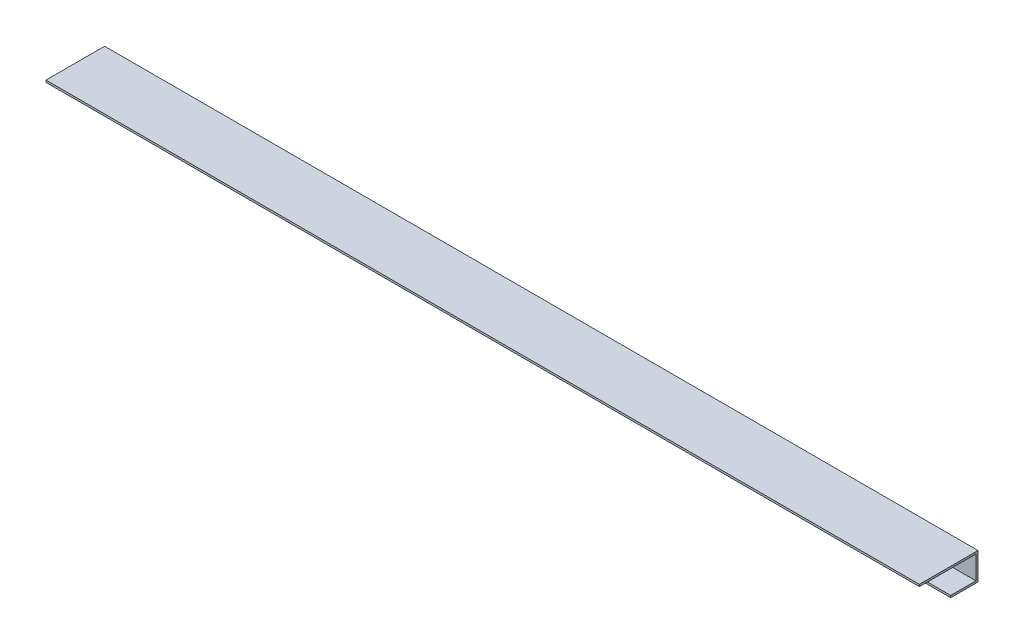
SolidWorks part; units mm, degrees
ref_plane "Front Plane" through (0, 0, 0) normal (0, 0, 1) x (1, 0, 0)
ref_plane "Top Plane" through (0, 0, 0) normal (0, 1, 0) x (1, 0, 0)
ref_plane "Right Plane" through (0, 0, 0) normal (1, 0, 0) x (0, 0, -1)
sketch "Sketch1" plane through (0, 0, 0) normal (1, 0, 0) x (0, 0, -1)
  line L0 (0, 0) -> (58, 0)
  line L1 (58, 0) -> (58, -27)
  line L2 (58, -27) -> (31, -27)
  line L3 (0, -2) -> (56, -2)
  line L4 (56, -2) -> (56, -25)
  line L5 (56, -25) -> (31, -25)
  line L6 (0, 0) -> (0, -2)
  line L7 (31, -25) -> (31, -27)
  dimension "D1" = 2
  dimension "D2" = 58
  dimension "D3" = 27
  dimension "D4" = 27
extrude "Boss-Extrude1" add sketch "Sketch1" along normal blind 864
equation "\"door_base_short7_R1_R_open_Single_width\"=864"
equation "\"D1@Boss-Extrude1\"=\"door_base_short7_R1_R_open_Single_width\""
equation "\"CarBeamWidth\"=700.0"
equation "\"WheelWidth\"=650.0"
equation "\"Wheel_FrontBoxDistance\"=1390.0"
equation "\"MetalSheet_3mm_length\"=5030.0"
equation "\"MetalSheet_3mm_width\"=1923.0"
equation "\"MetalSheet_3mm_FloorCut_L_length\"=1764.0"
equation "\"MetalSheet_3mm_FloorCut_L_disdance\"=1665.0"
equation "\"MetalSheet_3mm_FloorCut_R_length\"=1764.0"
equation "\"MetalSheet_3mm_FloorCut_R_disdance\"=1665.0"
equation "\"indoorHeight\"=1940.0"
equation "\"haveDoor_R\"=1"
equation "\"side_door_bottom_R_3mm_length\"=1934.0"
equation "\"1Bar_Side_RF_3mm_length\"=1493.0"
equation "\"1Bar_Side_RB_3mm_length\"=1493.0"
equation "\"DoorSeparator_RF_3mm_withHinge_toFrontDistance\"=1673.0"
equation "\"DoorSeparator_RF_3mm_withHinge_exist\"=1"
equation "\"DoorSeparator_RB_3mm_withHinge_toFrontDistance\"=3427.0"
equation "\"DoorSeparator_RB_3mm_withHinge_exist\"=1"
equation "\"Door_R1_L_open_Single_toFrontDistance\"=2547.5"
equation "\"Door_R1_L_open_Single_exist\"=1"
equation "\"door_base_long7_R1_L_open_Single_height\"=1890.0"
equation "\"door_base_short7_R1_L_open_Single_height\"=1890.0"
equation "\"door_base_short7_R1_L_open_Single_width\"=864"
equation "\"Door_R1_R_open_Single_toFrontDistance\"=3422.0"
equation "\"Door_R1_R_open_Single_exist\"=1"
equation "\"door_base_long7_R1_R_open_Single_height\"=1890.0"
equation "\"door_base_short7_R1_R_open_Single_height\"=1890.0"
equation "\"x\"=66.0"
equation "\"da\"=62.0"
equation "\"SquareTube_length\"=1923.0"
equation "\"channelSteel_length\"=5030.0"
equation "\"SquareTube_inFront_AvgDistance\"=285.0"
equation "\"SquareTube_inFront_TotalCount\"=5"
equation "\"SquareTube_inFront1_cutDepth50_R\"=0.5"
equation "\"SquareTube_inFront1_cutDepth50_L\"=0.5"
equation "\"SquareTube_inFront2_cutDepth50_R\"=0.5"
equation "\"SquareTube_inFront2_cutDepth50_L\"=0.5"
equation "\"SquareTube_inFront3_cutDepth50_R\"=0.5"
equation "\"SquareTube_inFront3_cutDepth50_L\"=0.5"
equation "\"SquareTube_inFront4_cutDepth50_R\"=0.5"
equation "\"SquareTube_inFront4_cutDepth50_L\"=0.5"
equation "\"SquareTube_inFront5_cutDepth50_R\"=50"
equation "\"SquareTube_inFront5_cutDepth50_L\"=50"
equation "\"SquareTube_inFront6_cutDepth50_R\"=50"
equation "\"SquareTube_inFront6_cutDepth50_L\"=50"
equation "\"SquareTube_inFront7_cutDepth50_R\"=50"
equation "\"SquareTube_inFront7_cutDepth50_L\"=50"
equation "\"SquareTube_inFront8_cutDepth50_R\"=50"
equation "\"SquareTube_inFront8_cutDepth50_L\"=50"
equation "\"SquareTube_inFront9_cutDepth50_R\"=50"
equation "\"SquareTube_inFront9_cutDepth50_L\"=50"
equation "\"SquareTube_inFront10_cutDepth50_R\"=50"
equation "\"SquareTube_inFront10_cutDepth50_L\"=50"
equation "\"SquareTube_inFront11_cutDepth50_R\"=50"
equation "\"SquareTube_inFront11_cutDepth50_L\"=50"
equation "\"SquareTube_inFront12_cutDepth50_R\"=50"
equation "\"SquareTube_inFront12_cutDepth50_L\"=50"
equation "\"SquareTube_inFront13_cutDepth50_R\"=50"
equation "\"SquareTube_inFront13_cutDepth50_L\"=50"
equation "\"SquareTube_inFront14_cutDepth50_R\"=50"
equation "\"SquareTube_inFront14_cutDepth50_L\"=50"
equation "\"SquareTube_inBack_AvgDistance\"=333.125"
equation "\"SquareTube_inBack_TotalCount\"=9"
equation "\"SquareTube_inBack1_cutDepth50_R\"=50"
equation "\"SquareTube_inBack1_cutDepth50_L\"=50"
equation "\"SquareTube_inBack2_cutDepth50_R\"=50"
equation "\"SquareTube_inBack2_cutDepth50_L\"=50"
equation "\"SquareTube_inBack3_cutDepth50_R\"=50"
equation "\"SquareTube_inBack3_cutDepth50_L\"=50"
equation "\"SquareTube_inBack4_cutDepth50_R\"=50"
equation "\"SquareTube_inBack4_cutDepth50_L\"=50"
equation "\"SquareTube_inBack5_cutDepth50_R\"=50"
equation "\"SquareTube_inBack5_cutDepth50_L\"=50"
equation "\"SquareTube_inBack6_cutDepth50_R\"=0.5"
equation "\"SquareTube_inBack6_cutDepth50_L\"=0.5"
equation "\"SquareTube_inBack7_cutDepth50_R\"=0.5"
equation "\"SquareTube_inBack7_cutDepth50_L\"=0.5"
equation "\"SquareTube_inBack8_cutDepth50_R\"=0.5"
equation "\"SquareTube_inBack8_cutDepth50_L\"=0.5"
